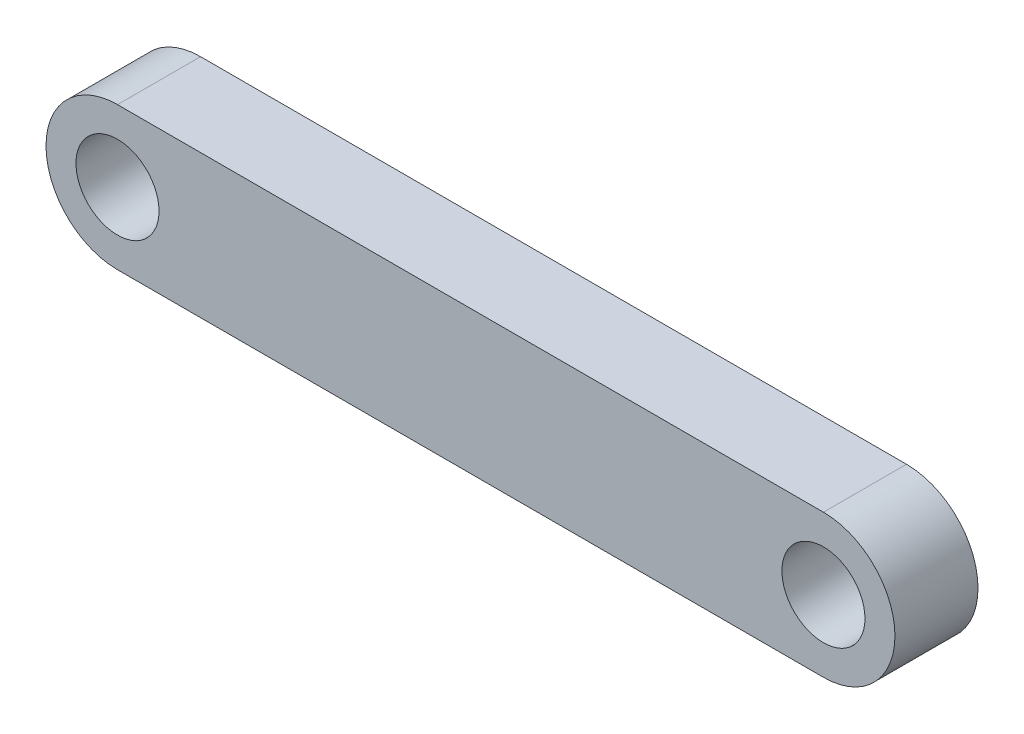
SolidWorks part; units mm, degrees
ref_plane "Front Plane" through (0, 0, 0) normal (0, 0, 1) x (1, 0, 0)
ref_plane "Top Plane" through (0, 0, 0) normal (0, 1, 0) x (1, 0, 0)
ref_plane "Right Plane" through (0, 0, 0) normal (1, 0, 0) x (0, 0, -1)
sketch "Sketch1" plane through (0, 0, 0) normal (0, 0, 1) x (1, 0, 0)
  line L0 (-8.91, 0) -> (8.09, 0) construction
  line L1 (-8.91, 1.7219) -> (8.09, 1.7219)
  line L2 (-8.91, -1.7219) -> (8.09, -1.7219)
  arc A0 (-8.91, 1.7219) -> (-8.91, -1.7219) centre (-8.91, 0) ccw
  arc A1 (8.09, -1.7219) -> (8.09, 1.7219) centre (8.09, 0) ccw
  circle A2 centre (8.09, 0) radius 1
  circle A3 centre (-8.91, 0) radius 1
  point P3 (-0.41, 0)
  dimension "D1" = 17
extrude "Boss-Extrude1" add sketch "Sketch1" along normal blind 2
